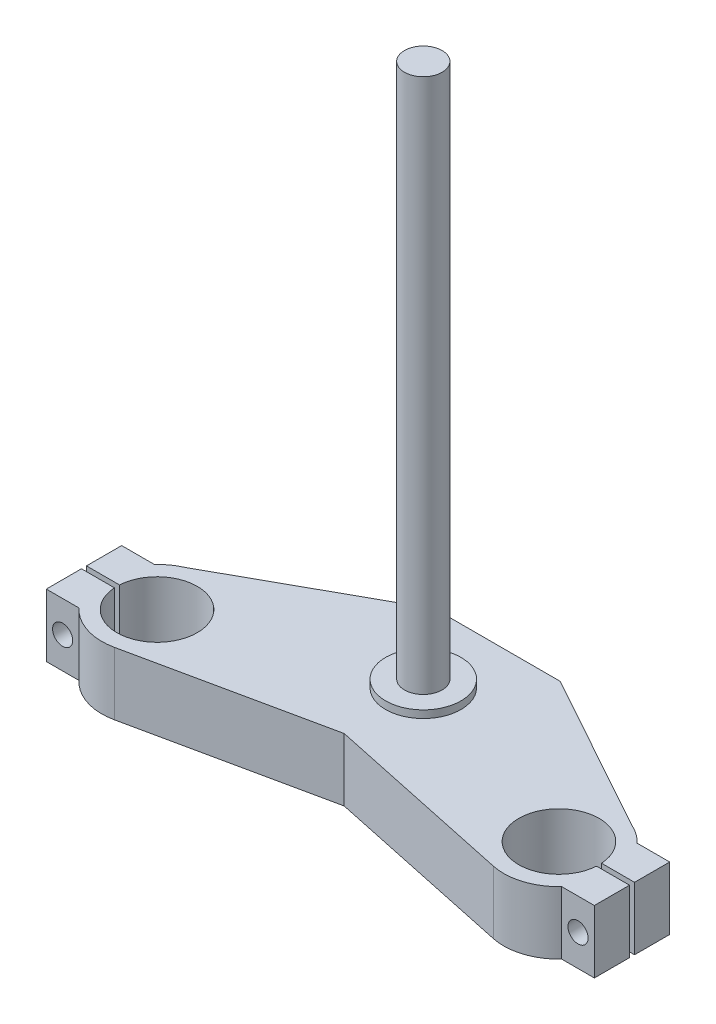
SolidWorks part; units mm, degrees
ref_plane "Front Plane" through (0, 0, 0) normal (0, 0, 1) x (1, 0, 0)
ref_plane "Top Plane" through (0, 0, 0) normal (0, 1, 0) x (1, 0, 0)
ref_plane "Right Plane" through (0, 0, 0) normal (1, 0, 0) x (0, 0, -1)
sketch "Sketch1" plane through (0, 0, 0) normal (0, 1, 0) x (1, 0, 0)
  line L0 (-25, 55.5) -> (-88.782, 20.1805)
  line L1 (-109.1052, 1) -> (-109.1052, 15)
  line L2 (25, 55.5) -> (88.782, 20.1805)
  line L3 (-75.4253, -21.5279) -> (0, -5.5)
  line L4 (25, 55.5) -> (1, 55.5)
  line L5 (-109.1052, -1) -> (-109.1052, -15)
  line L6 (-109.1052, -15) -> (-96.1052, -15)
  line L7 (-109.1052, 15) -> (-96.1052, 15)
  line L8 (-1, 55.5) -> (-25, 55.5)
  line L9 (75.4253, -21.5279) -> (0, -5.5)
  line L10 (109.1052, 15) -> (96.1052, 15)
  line L11 (109.1052, -15) -> (96.1052, -15)
  line L12 (109.1052, -1) -> (109.1052, -15)
  line L14 (109.1052, 1) -> (109.1052, 15)
  line L16 (-109.1052, 1) -> (-95.9687, 1)
  line L17 (-109.1052, -1) -> (-95.9687, -1)
  line L18 (109.1052, 1) -> (95.9687, 1)
  line L19 (109.1052, -1) -> (95.9687, -1)
  line L22 (-1, 55.5) -> (1, 55.5)
  arc A0 (-95.9687, -1) -> (-95.9687, 1) centre (-80, 0) ccw
  arc A1 (-96.1052, -15) -> (-75.4253, -21.5279) centre (-80, 0) ccw
  arc A2 (88.782, 20.1805) -> (96.1052, 15) centre (80, 0) cw
  arc A3 (95.9687, -1) -> (95.9687, 1) centre (80, 0) cw
  arc A5 (-88.782, 20.1805) -> (-96.1052, 15) centre (-80, 0) ccw
  arc A6 (96.1052, -15) -> (75.4253, -21.5279) centre (80, 0) cw
  dimension "D1" = 32
  dimension "D7" = 13
extrude "Boss-Extrude1" add sketch "Sketch1" along normal blind 25
sketch "Sketch3" plane through (0, 0, 0) normal (0, 0, 1) x (1, 0, 0)
  circle A0 centre (-102.6052, 12.5) radius 4
  circle A1 centre (102.6052, 12.5) radius 4
  dimension "D1" = 8
extrude "Cut-Extrude1" cut sketch "Sketch3" against normal mid plane 30
sketch "Sketch4" plane through (0, 25, 0) normal (0, 1, 0) x (1, 0, 0)
  circle A0 centre (0, 26) radius 15
  dimension "D2" = 30
  dimension "D1" = 31.5
extrude "Boss-Extrude2" add sketch "Sketch4" along normal blind 3
sketch "Sketch5" plane through (0, 28, 0) normal (0, 1, 0) x (1, 0, 0)
  circle A0 centre (0, 26) radius 7.5
  dimension "D1" = 15
extrude "Boss-Extrude3" add sketch "Sketch5" along normal blind 213
